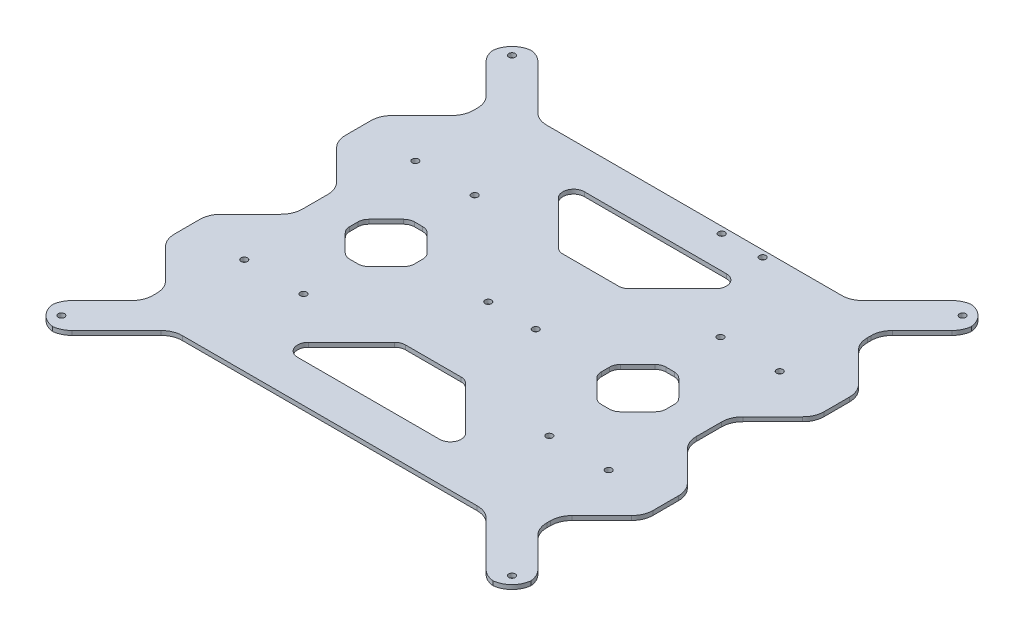
SolidWorks part; units mm, degrees
ref_plane "Front Plane" through (0, 0, 0) normal (0, 0, 1) x (1, 0, 0)
ref_plane "Top Plane" through (0, 0, 0) normal (0, 1, 0) x (1, 0, 0)
ref_plane "Right Plane" through (0, 0, 0) normal (1, 0, 0) x (0, 0, -1)
sketch "Sketch1" plane through (0, 0, 0) normal (0, 1, 0) x (1, 0, 0)
  line L0 (-111, 101) -> (-111, 103.1421)
  line L1 (-101, -111) -> (-103.1421, -111)
  line L2 (111, -103.1421) -> (111, -101)
  line L3 (101, 111) -> (103.1421, 111)
  line L4 (-108.0711, 96.0711) -> (-94.2623, 82.2623)
  line L5 (-91.3333, 75.1912) -> (-91.3333, 73.4755)
  line L6 (-94.2623, 66.4044) -> (-108.0711, 52.5956)
  line L7 (-108.0711, 26.7377) -> (-94.2623, 12.9289)
  line L8 (-91.3333, 5.8579) -> (-91.3333, -5.8579)
  line L9 (-94.2623, -12.9289) -> (-108.0711, -26.7377)
  line L10 (-108.0711, -52.5956) -> (-94.2623, -66.4044)
  line L11 (-91.3333, -73.4755) -> (-91.3333, -75.1912)
  line L12 (-94.2623, -82.2623) -> (-108.0711, -96.0711)
  line L13 (-91.3333, 0) -> (111, 0) construction
  line L14 (-111, 45.5245) -> (-111, 33.8088)
  line L15 (-111, -33.8088) -> (-111, -45.5245)
  line L16 (-111, -103.1421) -> (-111, -101)
  line L17 (111, 111) -> (-111, -111) construction
  line L18 (0, 84.5) -> (0, 0) construction
  line L19 (94.2623, -82.2623) -> (108.0711, -96.0711)
  line L20 (91.3333, -73.4755) -> (91.3333, -75.1912)
  line L21 (108.0711, -52.5956) -> (94.2623, -66.4044)
  line L22 (111, -33.8088) -> (111, -45.5245)
  line L23 (94.2623, -12.9289) -> (108.0711, -26.7377)
  line L24 (91.3333, 5.8579) -> (91.3333, -5.8579)
  line L25 (108.0711, 26.7377) -> (94.2623, 12.9289)
  line L26 (111, 45.5245) -> (111, 33.8088)
  line L27 (94.2623, 66.4044) -> (108.0711, 52.5956)
  line L28 (91.3333, 75.1912) -> (91.3333, 73.4755)
  line L29 (108.0711, 96.0711) -> (94.2623, 82.2623)
  line L30 (111, 101) -> (111, 103.1421)
  line L31 (-96.0711, -108.0711) -> (-75.4289, -87.4289)
  line L32 (-68.3579, -84.5) -> (68.3579, -84.5)
  line L33 (75.4289, -87.4289) -> (96.0711, -108.0711)
  line L34 (103.1421, -111) -> (101, -111)
  line L35 (75.4289, 87.4289) -> (96.0711, 108.0711)
  line L36 (-68.3579, 84.5) -> (68.3579, 84.5)
  line L37 (-96.0711, 108.0711) -> (-75.4289, 87.4289)
  line L38 (-103.1421, 111) -> (-101, 111)
  line L39 (-111, 111) -> (111, -111) construction
  line L40 (-111, 39.6667) -> (-57, 39.6667) construction
  line L41 (-111, -39.6667) -> (-57, -39.6667) construction
  line L42 (111, -39.6667) -> (57, -39.6667) construction
  line L43 (111, 39.6667) -> (57, 39.6667) construction
  line L44 (-84.5, 39.6667) -> (-84.5, -39.6667) construction
  line L45 (84.5, 39.6667) -> (84.5, -39.6667) construction
  line L46 (57, 39.6667) -> (57, -39.6667) construction
  line L47 (-57, 39.6667) -> (-57, -39.6667) construction
  line L48 (-84.5, 39.6667) -> (-57, -39.6667) construction
  line L49 (57, 39.6667) -> (84.5, -39.6667) construction
  line L50 (-32.9289, 66.5) -> (32.9289, 66.5)
  line L51 (36.4645, 57.9645) -> (16.4645, 37.9645)
  line L52 (12.9289, 36.5) -> (-12.9289, 36.5)
  line L53 (-16.4645, 37.9645) -> (-36.4645, 57.9645)
  line L54 (12.9289, -36.5) -> (-12.9289, -36.5)
  line L55 (36.4645, -57.9645) -> (16.4645, -37.9645)
  line L56 (-32.9289, -66.5) -> (32.9289, -66.5)
  line L57 (-16.4645, -37.9645) -> (-36.4645, -57.9645)
  line L58 (-60.2623, 15) -> (-56.4044, 15)
  line L59 (-52.8689, 13.5355) -> (-44.7978, 5.4645)
  line L60 (-43.3333, 1.9289) -> (-43.3333, -1.9289)
  line L61 (-44.7978, -5.4645) -> (-52.8689, -13.5355)
  line L62 (-56.4044, -15) -> (-60.2623, -15)
  line L63 (-63.7978, -13.5355) -> (-71.8689, -5.4645)
  line L64 (-73.3333, -1.9289) -> (-73.3333, 1.9289)
  line L65 (-71.8689, 5.4645) -> (-63.7978, 13.5355)
  line L66 (-58.3333, 15) -> (-58.3333, -15) construction
  line L67 (73.3333, -1.9289) -> (73.3333, 1.9289)
  line L68 (63.7978, -13.5355) -> (71.8689, -5.4645)
  line L69 (56.4044, -15) -> (60.2623, -15)
  line L70 (44.7978, -5.4645) -> (52.8689, -13.5355)
  line L71 (43.3333, 1.9289) -> (43.3333, -1.9289)
  line L72 (52.8689, 13.5355) -> (44.7978, 5.4645)
  line L73 (60.2623, 15) -> (56.4044, 15)
  line L74 (71.8689, 5.4645) -> (63.7978, 13.5355)
  line L75 (15.75, 81.5) -> (34.75, 81.5) construction
  circle A0 centre (104.5, -104.5) radius 1.5
  circle A1 centre (-104.5, -104.5) radius 1.5
  circle A2 centre (104.5, 104.5) radius 1.5
  circle A3 centre (-104.5, 104.5) radius 1.5
  circle A4 centre (-84.5, 39.6667) radius 1.5
  circle A5 centre (-57, 39.6667) radius 1.5
  circle A6 centre (57, 39.6667) radius 1.5
  circle A7 centre (84.5, 39.6667) radius 1.5
  circle A8 centre (-57, -39.6667) radius 1.5
  circle A9 centre (-84.5, -39.6667) radius 1.5
  circle A10 centre (57, -39.6667) radius 1.5
  circle A11 centre (84.5, -39.6667) radius 1.5
  arc A12 (12.9289, 36.5) -> (16.4645, 37.9645) centre (12.9289, 41.5) ccw
  arc A13 (-12.9289, 36.5) -> (-16.4645, 37.9645) centre (-12.9289, 41.5) cw
  arc A14 (32.9289, 66.5) -> (36.4645, 57.9645) centre (32.9289, 61.5) cw
  arc A15 (-32.9289, 66.5) -> (-36.4645, 57.9645) centre (-32.9289, 61.5) ccw
  arc A16 (-12.9289, -36.5) -> (-16.4645, -37.9645) centre (-12.9289, -41.5) ccw
  arc A17 (12.9289, -36.5) -> (16.4645, -37.9645) centre (12.9289, -41.5) cw
  arc A18 (32.9289, -66.5) -> (36.4645, -57.9645) centre (32.9289, -61.5) ccw
  arc A19 (-32.9289, -66.5) -> (-36.4645, -57.9645) centre (-32.9289, -61.5) cw
  arc A20 (-71.8689, 5.4645) -> (-73.3333, 1.9289) centre (-68.3333, 1.9289) ccw
  arc A21 (-73.3333, -1.9289) -> (-71.8689, -5.4645) centre (-68.3333, -1.9289) ccw
  arc A22 (-63.7978, -13.5355) -> (-60.2623, -15) centre (-60.2623, -10) ccw
  arc A23 (-56.4044, -15) -> (-52.8689, -13.5355) centre (-56.4044, -10) ccw
  arc A24 (-44.7978, -5.4645) -> (-43.3333, -1.9289) centre (-48.3333, -1.9289) ccw
  arc A25 (-43.3333, 1.9289) -> (-44.7978, 5.4645) centre (-48.3333, 1.9289) ccw
  arc A26 (-52.8689, 13.5355) -> (-56.4044, 15) centre (-56.4044, 10) ccw
  arc A27 (-60.2623, 15) -> (-63.7978, 13.5355) centre (-60.2623, 10) ccw
  arc A28 (71.8689, 5.4645) -> (73.3333, 1.9289) centre (68.3333, 1.9289) cw
  arc A29 (73.3333, -1.9289) -> (71.8689, -5.4645) centre (68.3333, -1.9289) cw
  arc A30 (63.7978, -13.5355) -> (60.2623, -15) centre (60.2623, -10) cw
  arc A31 (56.4044, -15) -> (52.8689, -13.5355) centre (56.4044, -10) cw
  arc A32 (44.7978, -5.4645) -> (43.3333, -1.9289) centre (48.3333, -1.9289) cw
  arc A33 (43.3333, 1.9289) -> (44.7978, 5.4645) centre (48.3333, 1.9289) cw
  arc A34 (52.8689, 13.5355) -> (56.4044, 15) centre (56.4044, 10) cw
  arc A35 (60.2623, 15) -> (63.7978, 13.5355) centre (60.2623, 10) cw
  arc A36 (68.3579, 84.5) -> (75.4289, 87.4289) centre (68.3579, 94.5) ccw
  arc A37 (103.1421, 111) -> (96.0711, 108.0711) centre (103.1421, 101) ccw
  arc A38 (101, 111) -> (111, 101) centre (101, 101) cw
  arc A39 (111, 103.1421) -> (108.0711, 96.0711) centre (101, 103.1421) cw
  arc A40 (94.2623, 82.2623) -> (91.3333, 75.1912) centre (101.3333, 75.1912) ccw
  arc A41 (91.3333, 73.4755) -> (94.2623, 66.4044) centre (101.3333, 73.4755) ccw
  arc A42 (108.0711, 52.5956) -> (111, 45.5245) centre (101, 45.5245) cw
  arc A43 (111, 33.8088) -> (108.0711, 26.7377) centre (101, 33.8088) cw
  arc A44 (94.2623, 12.9289) -> (91.3333, 5.8579) centre (101.3333, 5.8579) ccw
  arc A45 (91.3333, -5.8579) -> (94.2623, -12.9289) centre (101.3333, -5.8579) ccw
  arc A46 (108.0711, -26.7377) -> (111, -33.8088) centre (101, -33.8088) cw
  arc A47 (108.0711, -52.5956) -> (111, -45.5245) centre (101, -45.5245) ccw
  arc A48 (91.3333, -73.4755) -> (94.2623, -66.4044) centre (101.3333, -73.4755) cw
  arc A49 (91.3333, -75.1912) -> (94.2623, -82.2623) centre (101.3333, -75.1912) ccw
  arc A50 (108.0711, -96.0711) -> (111, -103.1421) centre (101, -103.1421) cw
  arc A51 (111, -101) -> (101, -111) centre (101, -101) cw
  arc A52 (103.1421, -111) -> (96.0711, -108.0711) centre (103.1421, -101) cw
  arc A53 (75.4289, -87.4289) -> (68.3579, -84.5) centre (68.3579, -94.5) ccw
  arc A54 (-68.3579, -84.5) -> (-75.4289, -87.4289) centre (-68.3579, -94.5) ccw
  arc A55 (-103.1421, -111) -> (-96.0711, -108.0711) centre (-103.1421, -101) ccw
  arc A56 (-101, -111) -> (-111, -101) centre (-101, -101) cw
  arc A57 (-111, -103.1421) -> (-108.0711, -96.0711) centre (-101, -103.1421) cw
  arc A58 (-91.3333, -75.1912) -> (-94.2623, -82.2623) centre (-101.3333, -75.1912) cw
  arc A59 (-91.3333, -73.4755) -> (-94.2623, -66.4044) centre (-101.3333, -73.4755) ccw
  arc A60 (-108.0711, -52.5956) -> (-111, -45.5245) centre (-101, -45.5245) cw
  arc A61 (-111, -33.8088) -> (-108.0711, -26.7377) centre (-101, -33.8088) cw
  arc A62 (-94.2623, -12.9289) -> (-91.3333, -5.8579) centre (-101.3333, -5.8579) ccw
  arc A63 (-94.2623, 12.9289) -> (-91.3333, 5.8579) centre (-101.3333, 5.8579) cw
  arc A64 (-111, 33.8088) -> (-108.0711, 26.7377) centre (-101, 33.8088) ccw
  arc A65 (-111, 45.5245) -> (-108.0711, 52.5956) centre (-101, 45.5245) cw
  arc A66 (-91.3333, 73.4755) -> (-94.2623, 66.4044) centre (-101.3333, 73.4755) cw
  arc A67 (-91.3333, 75.1912) -> (-94.2623, 82.2623) centre (-101.3333, 75.1912) ccw
  arc A68 (-68.3579, 84.5) -> (-75.4289, 87.4289) centre (-68.3579, 94.5) cw
  arc A69 (-103.1421, 111) -> (-96.0711, 108.0711) centre (-103.1421, 101) cw
  arc A70 (-111, 103.1421) -> (-108.0711, 96.0711) centre (-101, 103.1421) ccw
  arc A71 (-101, 111) -> (-111, 101) centre (-101, 101) ccw
  circle A72 centre (-11, 0) radius 1.5
  circle A73 centre (11, 0) radius 1.5
  circle A74 centre (15.75, 81.5) radius 1.5
  circle A75 centre (34.75, 81.5) radius 1.5
  point P79 (45, 66.5)
  point P82 (-45, 66.5)
  point P115 (-43.3333, -4)
  point P118 (-43.3333, 4)
  point P121 (-54.3333, 15)
  point P124 (-62.3333, 15)
  point P151 (72.5, 84.5)
  point P154 (99, 111)
  point P160 (111, 99)
  point P163 (91.3333, 79.3333)
  point P166 (91.3333, 69.3333)
  point P169 (111, 49.6667)
  point P172 (111, 29.6667)
  point P175 (91.3333, 10)
  point P178 (91.3333, -10)
  point P181 (111, -29.6667)
  point P184 (111, -49.6667)
  point P187 (91.3333, -69.3333)
  point P190 (91.3333, -79.3333)
  point P193 (111, -99)
  point P199 (99, -111)
  point P202 (72.5, -84.5)
  point P205 (-72.5, -84.5)
  point P208 (-99, -111)
  point P214 (-111, -99)
  point P217 (-91.3333, -79.3333)
  point P220 (-91.3333, -69.3333)
  point P223 (-111, -49.6667)
  point P226 (-111, -29.6667)
  point P229 (-91.3333, -10)
  point P232 (-91.3333, 10)
  point P235 (-111, 29.6667)
  point P238 (-111, 49.6667)
  point P241 (-91.3333, 69.3333)
  point P244 (-91.3333, 79.3333)
  point P247 (-72.5, 84.5)
  point P250 (-99, 111)
  point P253 (-111, 99)
  dimension "D13" = 3
  dimension "D17" = 3
  dimension "D22" = 5
  dimension "D27" = 5
  dimension "D28" = 10
  dimension "D29" = 3
  dimension "D30" = 22
  dimension "D31" = 3
  dimension "D1" = 45
  dimension "D2" = 45
  dimension "D3" = 45
  dimension "D4" = 222
  dimension "D5" = 20
  dimension "D6" = 12
  dimension "D7" = 20
  dimension "D8" = 10
  dimension "D9" = 222
  dimension "D10" = 45
  dimension "D11" = 145
  dimension "D12" = 12
  dimension "D14" = 209
  dimension "D15" = 27.5
  dimension "D16" = 54
  dimension "D18" = 18
  dimension "D19" = 45
  dimension "D20" = 30
  dimension "D21" = 90
  dimension "D23" = 33
  dimension "D24" = 8
  dimension "D25" = 8
  dimension "D26" = 30
  dimension "D32" = 19
  dimension "D33" = 3
  dimension "D34" = 75.5833
extrude "Boss-Extrude1" add sketch "Sketch1" along normal blind 2 contours A69 A71 A70 L4 A67 L5 A66 L6 A65 L14 A64 L7 A63 L8 A62 L9 A61 L15 A60 L10 A59 L11 A58 L12 A57 A56 A55 L31 A54 L32 A53 L33 A52 A51 A50 L19 A49 L20 A48 L21 A47 L22 A46 L23 A45 L24 A44 L25 A43 L26 A42
